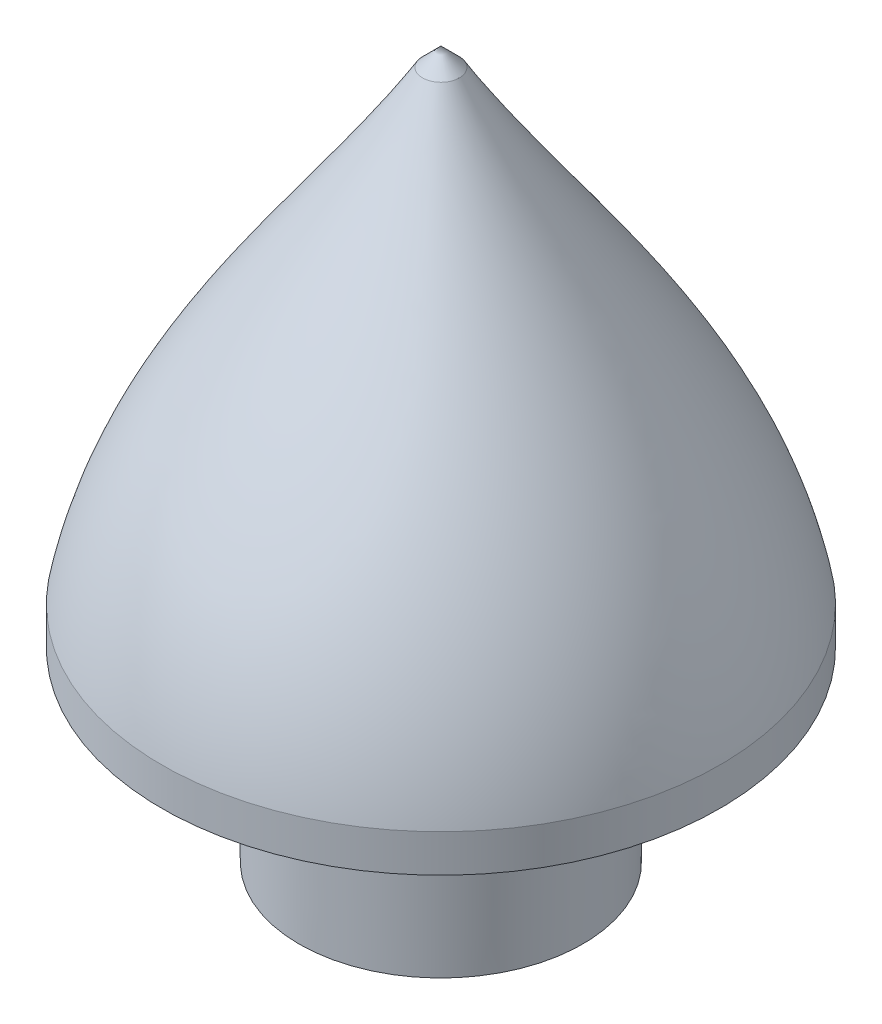
SolidWorks part; units mm, degrees
ref_plane "Front Plane" through (0, 0, 0) normal (0, 0, 1) x (1, 0, 0)
ref_plane "Top Plane" through (0, 0, 0) normal (0, 1, 0) x (1, 0, 0)
ref_plane "Right Plane" through (0, 0, 0) normal (1, 0, 0) x (0, 0, -1)
sketch "Sketch1" plane through (0, 0, 0) normal (0, 0, 1) x (1, 0, 0)
  line L0 (0, 0) -> (0, -2) construction
  line L1 (0, 0) -> (0, 7) construction
  line L2 (0, -2) -> (-2, -2)
  line L3 (-2, -2) -> (-2, 0)
  line L4 (-2, 0) -> (-3.75, 0)
  line L5 (-3.75, 0) -> (-3.75, 0.5063)
  line L6 (0, 7) -> (-0.2474, 6.7526)
  line L7 (0, -2) -> (0, 7)
  spline S0 degree 3 poles (-0.2474, 6.7526) (-1.4798, 4.7089) (-3.2829, 2.9489) (-3.75, 0.5063) knots 0 0 0 0 1 1 1 1
  dimension "D1" = 2
  dimension "D2" = 7
  dimension "D3" = 2
  dimension "D4" = 3.75
revolve "Revolve1" add sketch "Sketch1" angle 360 about L7
sketch "Sketch2" plane through (0, -2, 0) normal (0, -1, 0) x (1, 0, 0)
  circle A0 centre (0, 0) radius 2.1
extrude "Cut-Extrude1" cut sketch "Sketch2" against normal blind 2
shell "Shell1" [suppressed] thickness 1.65
sketch "Sketch3" plane through (0, 0, 0) normal (0, -1, 0) x (1, 0, 0)
  circle A0 centre (0, 0) radius 2.1
  circle A1 centre (0, 0) radius 2.95
extrude "Boss-Extrude1" [suppressed] add sketch "Sketch3" along normal blind 13.5
fillet "Fillet1" [suppressed] radius 0.5
sketch "Sketch4" plane through (0, 0, 0) normal (0, -1, 0) x (1, 0, 0)
  circle A0 centre (0, 0) radius 1.95
  dimension "D1" = 3.9
extrude "Boss-Extrude2" add sketch "Sketch4" along normal blind 2.5 draft 1
